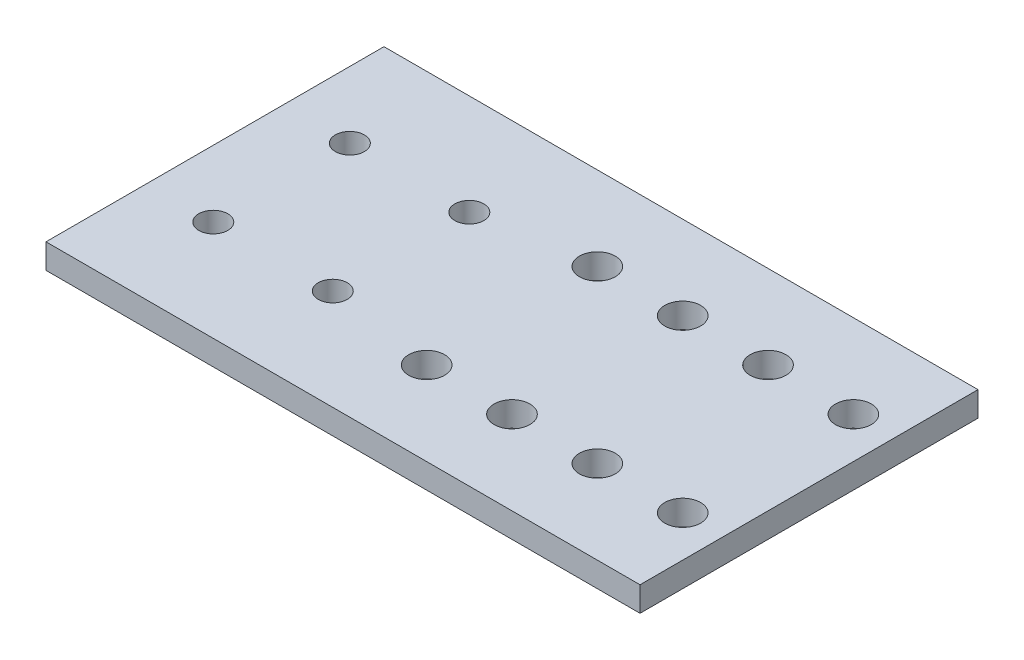
SolidWorks part; units mm, degrees
ref_plane "前视基准面" through (0, 0, 0) normal (0, 0, 1) x (1, 0, 0)
ref_plane "上视基准面" through (0, 0, 0) normal (0, 1, 0) x (1, 0, 0)
ref_plane "右视基准面" through (0, 0, 0) normal (1, 0, 0) x (0, 0, -1)
other "Configuration Table"
sketch "草图1" plane through (0, 0, 0) normal (0, 1, 0) x (1, 0, 0)
  line L0 (0, 120) -> (0, -49880) construction
  line L1 (-100, -120) -> (100, -120)
  line L2 (-100, -120) -> (-100, 120)
  line L3 (-100, 120) -> (100, 120)
  line L4 (100, -120) -> (100, 120)
  line L5 (-100, -120) -> (100, 120) construction
  line L6 (-100, 120) -> (100, -120) construction
  line L7 (-100, 120) -> (-70, 120)
  line L8 (-100, 120) -> (-100, 80)
  line L9 (-100, 80) -> (-70, 80)
  line L10 (-70, 120) -> (-70, 80)
  line L11 (-65, 0) -> (49935, 0) construction
  line L12 (-70, 120) -> (-70, 113)
  line L13 (-70, 113) -> (-70, 87)
  line L14 (-70, 87) -> (-70, 80)
  line L15 (-70, 113) -> (-40, 113)
  line L16 (-40, 113) -> (-40, 87)
  line L17 (-40, 87) -> (-70, 87)
  line L18 (-70, 113) -> (-70, 108)
  line L19 (-70, 87) -> (-70, 92)
  line L20 (-40, 87) -> (-48, 87)
  line L21 (-48, 87) -> (-48, 92)
  line L22 (-48, 92) -> (-40, 92)
  line L23 (-70, 92) -> (-62, 92)
  line L24 (-62, 92) -> (-62, 87)
  line L25 (-70, 100) -> (-40, 100) construction
  line L26 (0, 120) -> (0, 0)
  line L27 (0, 0) -> (-100, 0)
  line L28 (-70, 80) -> (0, 80)
  line L29 (100, 80) -> (70, 80)
  line L30 (70, 120) -> (70, 80)
  line L31 (100, -80) -> (70, -80)
  line L32 (70, -120) -> (70, -80)
  line L33 (-70, -120) -> (-70, -80)
  line L34 (-100, -80) -> (-70, -80)
  line L35 (0, 120) -> (0, 100)
  line L36 (0, 100) -> (-25, 100)
  line L37 (-25, 100) -> (-25, 115)
  line L38 (-25, 100) -> (-25, 85)
  line L39 (-25, 85) -> (-5, 85)
  line L40 (-25, 115) -> (-5, 115)
  line L41 (-5, 115) -> (-5, 85)
  line L42 (5, 115) -> (5, 85)
  line L43 (25, 100) -> (25, 85)
  line L44 (25, 85) -> (5, 85)
  line L45 (25, 115) -> (5, 115)
  line L46 (25, 100) -> (25, 115)
  line L47 (25, -85) -> (5, -85)
  line L48 (25, -100) -> (25, -85)
  line L49 (25, -100) -> (25, -115)
  line L50 (25, -115) -> (5, -115)
  line L51 (5, -115) -> (5, -85)
  line L52 (-25, -100) -> (-25, -115)
  line L53 (-25, -100) -> (-25, -85)
  line L54 (-25, -85) -> (-5, -85)
  line L55 (-5, -115) -> (-5, -85)
  line L56 (-25, -115) -> (-5, -115)
  line L57 (-100, 0) -> (-90, 0)
  line L58 (0, 120) -> (0, 100)
  line L59 (0, 120) -> (0, 110)
  line L60 (-70, 80) -> (0, 80)
  line L61 (-70, 113) -> (-20, 113)
  line L62 (-70, 80) -> (0, 80)
  line L63 (-20, 113) -> (-40, 113)
  line L64 (-20, 113) -> (-20, 87)
  line L65 (-20, 87) -> (-40, 87)
  line L66 (-40, 113) -> (-40, 87)
  line L67 (-20, 87) -> (-20, 80)
  line L68 (-20, 80) -> (-20, 120)
  circle A0 centre (-62, 92) radius 1.7
  circle A1 centre (-48, 92) radius 1.7
  circle A2 centre (-48, 108) radius 1.7
  circle A3 centre (-62, 108) radius 1.7
  circle A4 centre (48, 108) radius 1.7
  circle A5 centre (48, 92) radius 1.7
  circle A6 centre (62, 92) radius 1.7
  circle A7 centre (62, 108) radius 1.7
  circle A8 centre (62, -108) radius 1.7
  circle A9 centre (62, -92) radius 1.7
  circle A10 centre (48, -92) radius 1.7
  circle A11 centre (48, -108) radius 1.7
  circle A12 centre (-48, -92) radius 1.7
  circle A13 centre (-62, -92) radius 1.7
  circle A14 centre (-48, -108) radius 1.7
  circle A15 centre (-62, -108) radius 1.7
  circle A16 centre (-90, 0) radius 2.5
  circle A17 centre (-90, 50) radius 2.5
  circle A18 centre (-90, -50) radius 2.5
  circle A19 centre (90, -50) radius 2.5
  circle A20 centre (90, 0) radius 2.5
  circle A21 centre (90, 50) radius 2.5
  circle A22 centre (0, 110) radius 2.5
  circle A23 centre (35, 110) radius 2.5
  point P0 (0, 0)
  point P11 (0, 120)
  point P14 (-100, 0)
  point P15 (100, 0)
  dimension "D12" = 3.4
  dimension "D13" = 3.4
  dimension "D19" = 5
  dimension "D23" = 5
  dimension "D1" = 200
  dimension "D2" = 240
  dimension "D3" = 30
  dimension "D4" = 40
  dimension "D5" = 7
  dimension "D6" = 7
  dimension "D7" = 30
  dimension "D8" = 5
  dimension "D9" = 5
  dimension "D10" = 8
  dimension "D11" = 8
  dimension "D14" = 25
  dimension "D15" = 15
  dimension "D16" = 15
  dimension "D17" = 20
  dimension "D18" = 10
  dimension "D21" = 20
  dimension "D22" = 10
  dimension "D25" = 50
  dimension "D26" = 40
  dimension "D20" = 2
  dimension "D24" = 2
extrude "凸台-拉伸3" add sketch "草图1" along normal blind 2.9 contours A1 L22 L16 L15 L10 L13 L23 A0 L24 L17 L21 A2 A3 | A0 L23 L10 L17 L24 | A1 L21 L17 L16 L22 | L67 L39 L38 L65 L17 L10 L28 | L65 L38 L37 L61 L16 | L65 L64 L36 L38 | L64 L61 L37 L36 | L67 L65 L38 L39 | L40 L68 L3 L10 L15 L61 L37 | L61 L68 L40 L37
sketch "草图3" plane through (0, 2.9, 0) normal (0, 1, 0) x (1, 0, 0)
  line L0 (-1070, 100) -> (48930, 100)
  line L1 (-70, 120) -> (-70, 80) construction
  line L2 (-20, 100) -> (-20, 110)
  line L3 (-20, 120) -> (-20, 80) construction
  line L4 (-20, 110) -> (-25, 110)
  circle A0 centre (-25, 110) radius 2.1
  circle A1 centre (-25, 90) radius 2.1
  circle A2 centre (-35, 90) radius 2.1
  circle A3 centre (-35, 110) radius 2.1
  point P5 (-70, 100)
  dimension "D3" = 4.2
  dimension "D1" = 10
  dimension "D2" = 5
  dimension "D4" = 2
extrude "切除-拉伸3" cut sketch "草图3" against normal blind 2.9
sketch "草图4" plane through (0, 2.9, 0) normal (0, 1, 0) x (1, 0, 0)
  line L0 (-25, 110) -> (-15, 110)
  line L1 (-20, 120) -> (0, 120)
  line L2 (-20, 120) -> (-20, 80)
  line L3 (-20, 80) -> (0, 80)
  line L4 (0, 120) -> (0, 80)
  line L5 (-1020, 100) -> (48980, 100)
  circle A0 centre (-15, 110) radius 2.1
  circle A2 centre (-15, 90) radius 2.1
  circle A3 centre (-5, 110) radius 2.1
  circle A4 centre (-5, 90) radius 2.1
  point P12 (-20, 100)
  dimension "D3" = 4.2
  dimension "D1" = 20
  dimension "D2" = 10
  dimension "D4" = 2
extrude "凸台-拉伸4" add sketch "草图4" against normal blind 2.9
sketch "草图5" plane through (0, 2.9, 0) normal (0, 1, 0) x (1, 0, 0)
  line L0 (-69.8, 119.8) -> (-69.8, 80.2)
  line L1 (-70, 120) -> (0, 120)
  line L2 (-70, 120) -> (-70, 80)
  line L3 (-70, 80) -> (0, 80)
  line L4 (0, 120) -> (0, 80)
  line L5 (-69.8, 80.2) -> (-0.2, 80.2)
  line L6 (-0.2, 119.8) -> (-0.2, 80.2)
  line L7 (-69.8, 119.8) -> (-0.2, 119.8)
  dimension "D1" = 0.2
extrude "切除-拉伸4" cut sketch "草图5" against normal blind 2.9
